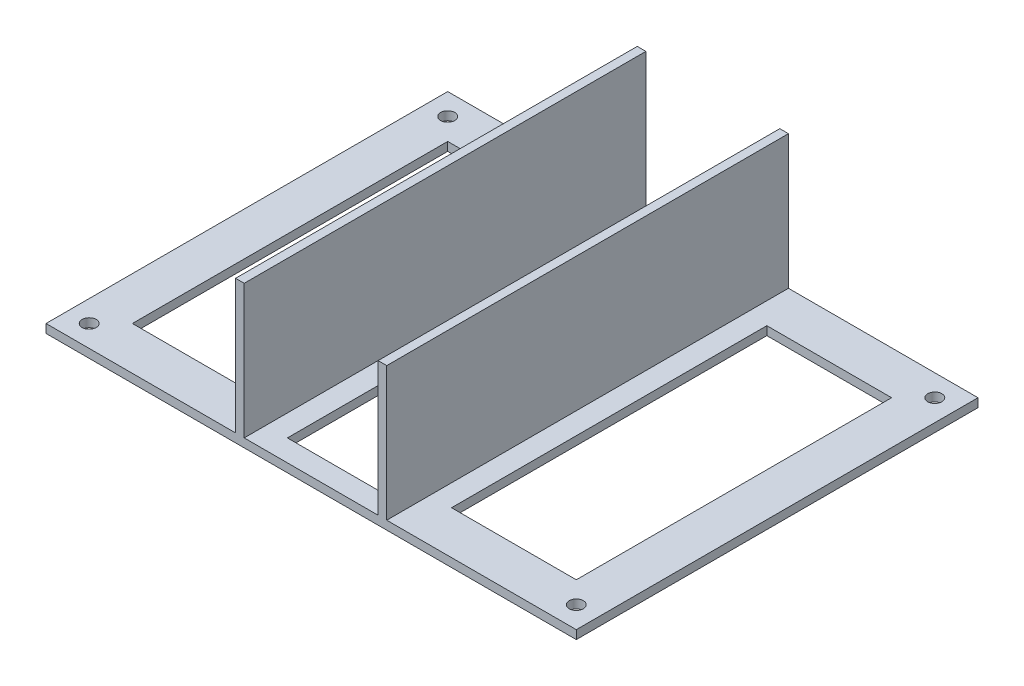
SolidWorks part; units mm, degrees
ref_plane "Front Plane" through (0, 0, 0) normal (0, 0, 1) x (1, 0, 0)
ref_plane "Top Plane" through (0, 0, 0) normal (0, 1, 0) x (1, 0, 0)
ref_plane "Right Plane" through (0, 0, 0) normal (1, 0, 0) x (0, 0, -1)
sketch "Sketch1" plane through (0, 0, 0) normal (0, 1, 0) x (1, 0, 0)
  line L0 (-161.7564, -41.1415) -> (-48.9864, 41.8585)
  line L1 (-161.7564, 41.8585) -> (-48.9864, 41.8585)
  line L2 (-161.7564, 41.8585) -> (-161.7564, -41.1415)
  line L3 (-161.7564, -41.1415) -> (-48.9864, -41.1415)
  line L4 (-48.9864, 41.8585) -> (-48.9864, -41.1415)
  line L5 (-161.7564, 41.8585) -> (-48.9864, -41.1415)
  line L7 (-166.7564, 46.8585) -> (-43.9864, 46.8585)
  line L8 (-166.7564, 46.8585) -> (-166.7564, -46.1415)
  line L9 (-166.7564, -46.1415) -> (-43.9864, -46.1415)
  line L10 (-43.9864, 46.8585) -> (-43.9864, -46.1415)
  circle A0 centre (-161.7564, 41.8585) radius 1.63
  circle A1 centre (-48.9864, 41.8585) radius 1.63
  circle A2 centre (-161.7564, -41.1415) radius 1.63
  circle A3 centre (-48.9864, -41.1415) radius 1.63
  dimension "D7" = 3.26
  dimension "D8" = 3.26
  dimension "D9" = 3.26
  dimension "D10" = 3.26
  dimension "D1" = 83
  dimension "D2" = 112.77
  dimension "D3" = 5
  dimension "D4" = 5
  dimension "D5" = 5
  dimension "D6" = 5
extrude "Boss-Extrude1" add sketch "Sketch1" along normal blind 2 contours L10 L7 L8 L9 A3 L3 A2 L2 A0 L1 A1 L4 | A1 L1 A0 L5 L0 | A3 L4 A1 L0 L5 | A3 L5 L0 A2 L3 | A2 L0 L5 A0 L2
sketch "Sketch2" plane through (0, 2, 0) normal (0, 1, 0) x (1, 0, 0)
  line L0 (-105.3714, -46.1415) -> (-105.3714, 46.8585)
  line L1 (-166.7564, 46.8585) -> (-43.9864, 46.8585)
  line L2 (-166.7564, 46.8585) -> (-166.7564, -46.1415)
  line L3 (-166.7564, -46.1415) -> (-43.9864, -46.1415)
  line L4 (-43.9864, 46.8585) -> (-43.9864, -46.1415)
  line L6 (-120.8714, -46.1415) -> (-89.8714, -46.1415)
  line L7 (-120.8714, -46.1415) -> (-120.8714, 46.8585)
  line L8 (-120.8714, 46.8585) -> (-89.8714, 46.8585)
  line L9 (-89.8714, -46.1415) -> (-89.8714, 46.8585)
  line L10 (-120.8714, -46.1415) -> (-89.8714, 46.8585) construction
  line L11 (-120.8714, 46.8585) -> (-89.8714, -46.1415) construction
  line L12 (-120.8714, 46.8585) -> (-122.8714, 46.8585)
  line L13 (-120.8714, 46.8585) -> (-120.8714, -46.1415)
  line L14 (-120.8714, -46.1415) -> (-122.8714, -46.1415)
  line L15 (-122.8714, 46.8585) -> (-122.8714, -46.1415)
  line L16 (-89.8714, 46.8585) -> (-87.8714, 46.8585)
  line L17 (-89.8714, 46.8585) -> (-89.8714, -46.1415)
  line L18 (-89.8714, -46.1415) -> (-87.8714, -46.1415)
  line L19 (-87.8714, 46.8585) -> (-87.8714, -46.1415)
  point P8 (-105.3714, 0.3585)
  dimension "D1" = 93
  dimension "D2" = 93
  dimension "D3" = 31
  dimension "D4" = 2
  dimension "D5" = 93
  dimension "D6" = 2
  dimension "D7" = 93
extrude "Boss-Extrude2" add sketch "Sketch2" along normal blind 31 contours L1 L15 L3 L7 | L16 L19 L18 L17
sketch "Sketch3" plane through (0, 2, 0) normal (0, 1, 0) x (1, 0, 0)
  line L0 (-120.8714, 46.8585) -> (-89.8714, 46.8585) construction
  line L1 (-156.7564, 36.8585) -> (-127.8714, 36.8585)
  line L2 (-156.7564, 36.8585) -> (-156.7564, -36.1415)
  line L3 (-156.7564, -36.1415) -> (-127.8714, -36.1415)
  line L4 (-127.8714, 36.8585) -> (-127.8714, -36.1415)
  line L5 (-94.8714, 41.8585) -> (-115.8714, 41.8585)
  line L6 (-94.8714, 41.8585) -> (-94.8714, -41.1415)
  line L7 (-94.8714, -41.1415) -> (-115.8714, -41.1415)
  line L8 (-115.8714, 41.8585) -> (-115.8714, -41.1415)
  line L9 (-82.8714, 36.8585) -> (-53.9864, 36.8585)
  line L10 (-82.8714, 36.8585) -> (-82.8714, -36.1415)
  line L11 (-82.8714, -36.1415) -> (-53.9864, -36.1415)
  line L12 (-53.9864, 36.8585) -> (-53.9864, -36.1415)
  line L13 (-120.8714, -46.1415) -> (-89.8714, -46.1415) construction
  line L14 (-120.8714, -46.1415) -> (-120.8714, 46.8585) construction
  line L15 (-89.8714, 46.8585) -> (-89.8714, -46.1415) construction
  line L16 (-122.8714, 46.8585) -> (-122.8714, -46.1415) construction
  line L17 (-87.8714, 46.8585) -> (-87.8714, -46.1415) construction
  circle A0 centre (-48.9864, -41.1415) radius 1.63 construction
  circle A1 centre (-48.9864, 41.8585) radius 1.63 construction
  circle A2 centre (-161.7564, -41.1415) radius 1.63 construction
  circle A4 centre (-161.7564, 41.8585) radius 1.63 construction
  dimension "D3" = 5
  dimension "D4" = 5
  dimension "D5" = 5
  dimension "D6" = 5
  dimension "D1" = 5
  dimension "D2" = 5
  dimension "D7" = 5
  dimension "D8" = 5
  dimension "D9" = 5
  dimension "D10" = 5
  dimension "D11" = 5
  dimension "D12" = 5
extrude "Cut-Extrude1" cut sketch "Sketch3" against normal through all
equation "\"D3@Sketch1\"=5"
equation "\"D4@Sketch1\"=5"
equation "\"D5@Sketch1\"=5"
equation "\"D6@Sketch1\"=5"
equation "\"D8@Sketch1\"=\"D7@Sketch1\""
equation "\"D9@Sketch1\"=\"D8@Sketch1\""
equation "\"D10@Sketch1\"=3.26mm"
equation "\"D3@Sketch2\"=31"
equation "\"D2@Sketch2\"=\"D1@Sketch2\""
equation "\"D4@Sketch2\"=2"
equation "\"D6@Sketch2\"=2"
equation "\"D7@Sketch2\"=\"D1@Sketch2\""
equation "\"D1@Sketch3\"=5"
equation "\"D2@Sketch3\"=5"
equation "\"D4@Sketch3\"=5"
equation "\"D5@Sketch3\"=5"
